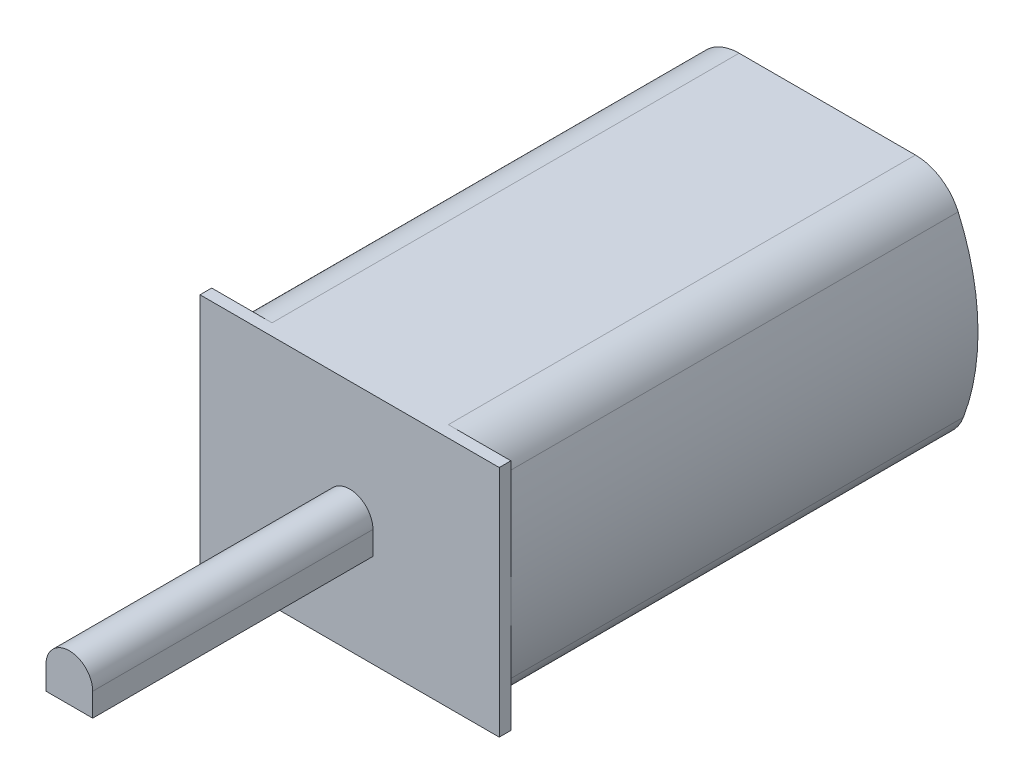
SolidWorks part; units mm, degrees
ref_plane "Front Plane" through (0, 0, 0) normal (0, 0, 1) x (1, 0, 0)
ref_plane "Top Plane" through (0, 0, 0) normal (0, 1, 0) x (1, 0, 0)
ref_plane "Right Plane" through (0, 0, 0) normal (1, 0, 0) x (0, 0, -1)
sketch "Sketch1" plane through (0, 0, 0) normal (0, 0, 1) x (1, 0, 0)
  line L0 (1.2441, 0) -> (8.9765, 0)
  line L1 (1.2441, 10) -> (8.7947, 10)
  arc A0 (-0.61, 1.25) -> (-0.61, 8.75) centre (8.6603, 5) cw
  arc A1 (10.8523, 1.3061) -> (10.625, 8.8061) centre (1.4733, 4.7754) ccw
  arc A2 (8.7947, 10) -> (10.625, 8.8061) centre (8.7947, 8) cw
  arc A3 (-0.61, 8.75) -> (1.2441, 10) centre (1.2441, 8) cw
  arc A4 (8.9765, 0) -> (10.8523, 1.3061) centre (8.9765, 2) ccw
  arc A5 (1.2441, 0) -> (-0.61, 1.25) centre (1.2441, 2) cw
  point P8 (10, 10)
  point P12 (0, 10)
  point P15 (10.2594, 0)
  point P18 (0, 0)
  dimension "D1" = 10
  dimension "D2" = 10
  dimension "D4" = 10
  dimension "D7" = 2
  dimension "D8" = 2
  dimension "D3" = 10
  dimension "D5" = 10
  dimension "D6" = 10.0034
extrude "Boss-Extrude1" add sketch "Sketch1" along normal blind 20
ref_plane "Plane1" through (0, 0, 20) normal (0, 0, 1) x (1, 0, 0)
sketch "Sketch3" plane through (0, 0, 20) normal (0, 0, 1) x (1, 0, 0)
  line L0 (8.7947, 10) -> (1.2441, 10) construction
  line L1 (-1.3397, 0) -> (11.4733, 0)
  line L2 (-1.3397, 0) -> (-1.3397, 10)
  line L3 (-1.3397, 10) -> (11.4733, 10)
  line L4 (11.4733, 0) -> (11.4733, 10)
  arc A0 (-0.61, 8.75) -> (-0.61, 1.25) centre (8.6603, 5) ccw construction
  arc A1 (10.8523, 1.3061) -> (10.625, 8.8061) centre (1.4733, 4.7754) ccw construction
  arc A2 (-0.61, 8.75) -> (-0.61, 1.25) centre (8.6603, 5) ccw
  arc A3 (10.8523, 1.3061) -> (10.625, 8.8061) centre (1.4733, 4.7754) ccw
  dimension "D1" = 10
extrude "Boss-Extrude2" add sketch "Sketch3" along normal blind 0.5
sketch "Sketch4" plane through (0, 0, 20.5) normal (0, 0, 1) x (1, 0, 0)
  line L0 (4.0653, 4) -> (6.0653, 4)
  line L1 (6.0653, 4) -> (6.0653, 5)
  line L2 (4.0653, 5) -> (4.0653, 4)
  line L3 (-1.3397, 0) -> (11.4733, 0) construction
  line L4 (-1.3397, 0) -> (-1.3397, 10) construction
  line L5 (11.4733, 0) -> (11.4733, 10) construction
  arc A0 (6.0653, 5) -> (4.0653, 5) centre (5.0653, 5) ccw
  point P12 (5.0653, 6)
  dimension "D1" = 5
  dimension "D2" = 6.405
  dimension "D3" = 6.4081
  dimension "D4" = 2
  dimension "D5" = 2
  dimension "D6" = 1
  dimension "D7" = 4
extrude "Boss-Extrude3" add sketch "Sketch4" along normal blind 12
